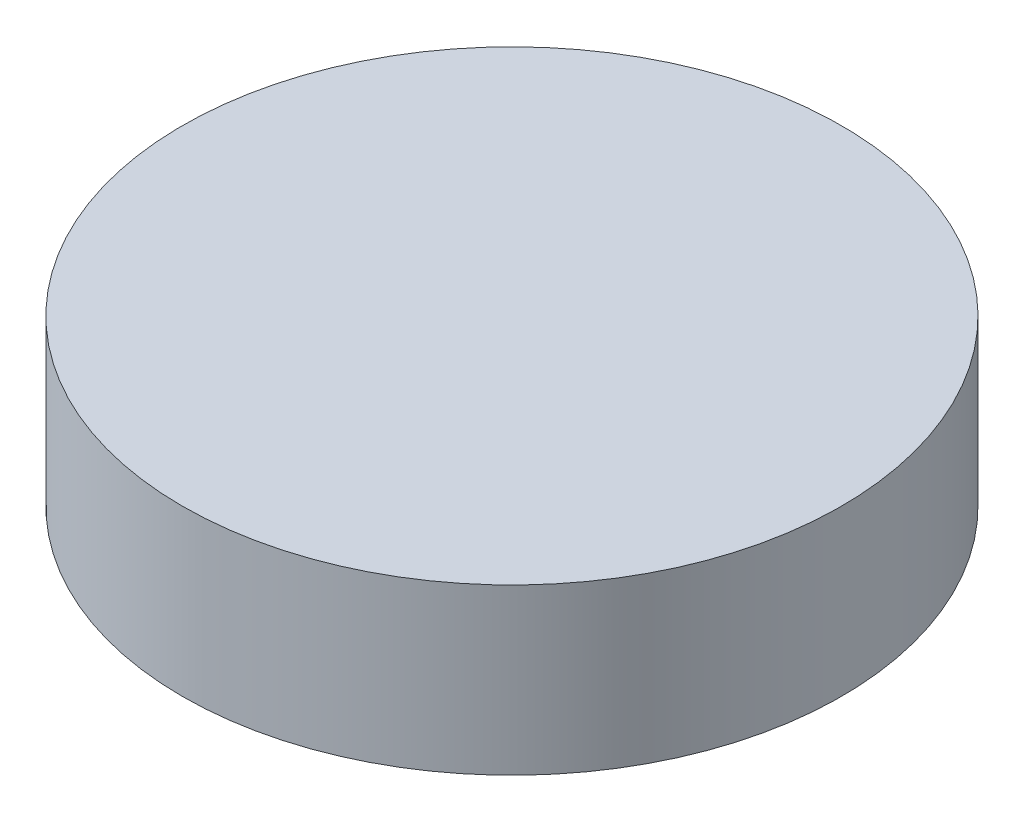
SolidWorks part; units mm, degrees
ref_plane "Front Plane" through (0, 0, 0) normal (0, 0, 1) x (1, 0, 0)
ref_plane "Top Plane" through (0, 0, 0) normal (0, 1, 0) x (1, 0, 0)
ref_plane "Right Plane" through (0, 0, 0) normal (1, 0, 0) x (0, 0, -1)
sketch "Sketch1" plane through (0, 0, 0) normal (0, 1, 0) x (1, 0, 0)
  circle A0 centre (0, 0) radius 6.35
  dimension "D1" = 12.7
extrude "Boss-Extrude1" add sketch "Sketch1" along normal blind 3.175 contours A0
